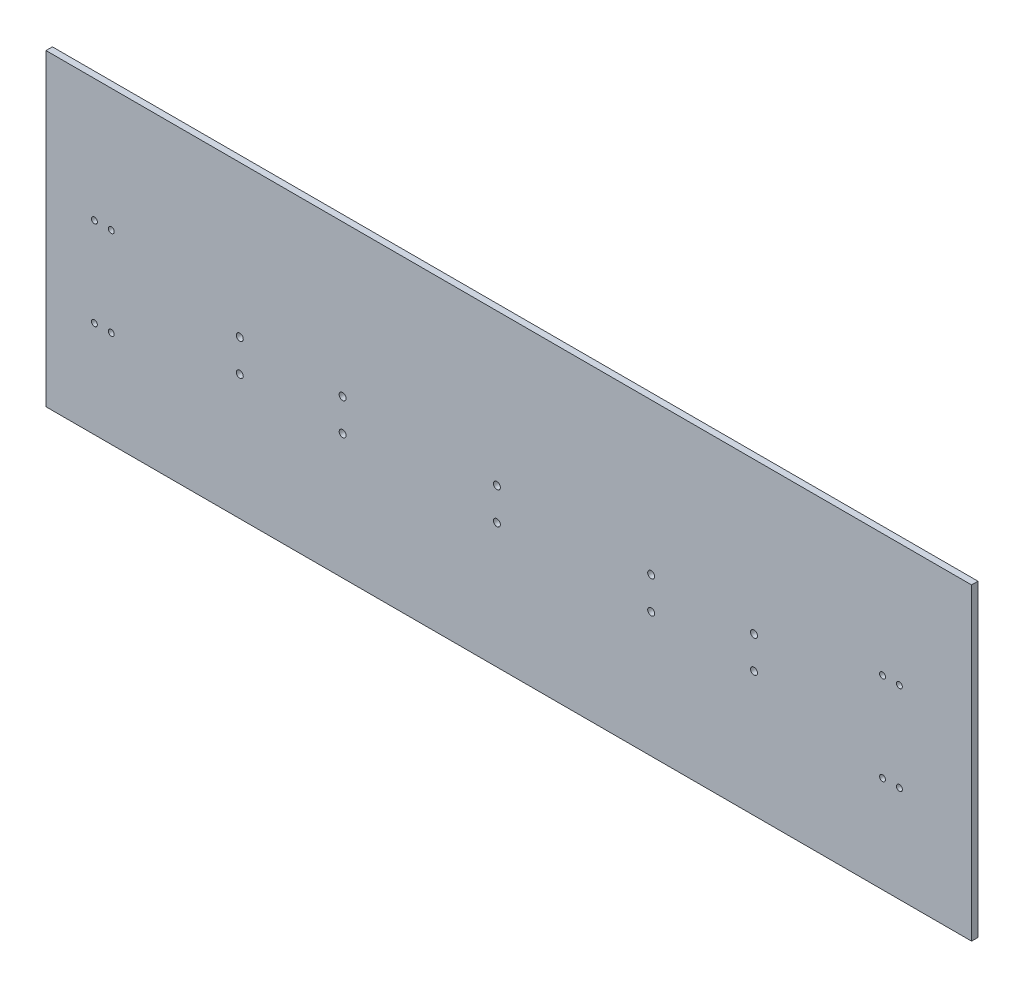
SolidWorks part; units mm, degrees
ref_plane "Front Plane" through (0, 0, 0) normal (0, 0, 1) x (1, 0, 0)
ref_plane "Top Plane" through (0, 0, 0) normal (0, 1, 0) x (1, 0, 0)
ref_plane "Right Plane" through (0, 0, 0) normal (1, 0, 0) x (0, 0, -1)
sketch "Sketch1" plane through (0, 0, 0) normal (0, 0, 1) x (1, 0, 0)
  line L0 (191.454, 155.3431) -> (191.454, 123.5931) construction
  line L1 (0, 0) -> (914.4, 0)
  line L2 (0, 0) -> (0, 304.8)
  line L3 (0, 304.8) -> (914.4, 304.8)
  line L4 (914.4, 0) -> (914.4, 304.8)
  line L5 (293.054, 155.3431) -> (293.054, 123.5931) construction
  line L6 (597.854, 155.3431) -> (597.854, 123.5931) construction
  line L7 (699.454, 155.3431) -> (699.454, 123.5931) construction
  line L8 (445.454, 155.3431) -> (445.454, 123.5931) construction
  line L9 (47.817, 183.4101) -> (64.454, 183.4101) construction
  line L10 (64.454, 183.4101) -> (64.454, 95.5261) construction
  line L11 (64.454, 95.5261) -> (47.817, 95.5261) construction
  line L12 (843.091, 183.4101) -> (826.454, 183.4101) construction
  line L13 (826.454, 183.4101) -> (826.454, 95.5261) construction
  line L14 (826.454, 95.5261) -> (843.091, 95.5261) construction
  line L15 (445.454, 139.4681) -> (597.854, 139.4681) construction
  line L16 (597.854, 139.4681) -> (699.454, 139.4681) construction
  line L17 (699.454, 139.4681) -> (826.454, 139.4681) construction
  line L18 (445.454, 139.4681) -> (293.054, 139.4681) construction
  line L19 (293.054, 139.4681) -> (191.454, 139.4681) construction
  line L20 (191.454, 139.4681) -> (64.454, 139.4681) construction
  circle A0 centre (445.454, 155.3431) radius 3.429
  circle A1 centre (445.454, 123.5931) radius 3.429
  circle A2 centre (597.854, 155.3431) radius 3.429
  circle A3 centre (597.854, 123.5931) radius 3.429
  circle A4 centre (699.454, 155.3431) radius 3.429
  circle A5 centre (699.454, 123.5931) radius 3.429
  circle A6 centre (293.054, 155.3431) radius 3.429
  circle A7 centre (293.054, 123.5931) radius 3.429
  circle A8 centre (191.454, 155.3431) radius 3.429
  circle A9 centre (191.454, 123.5931) radius 3.429
  circle A10 centre (47.817, 183.4101) radius 2.921
  circle A11 centre (64.454, 183.4101) radius 2.921
  circle A12 centre (47.817, 95.5261) radius 2.921
  circle A13 centre (64.454, 95.5261) radius 2.921
  circle A14 centre (826.454, 183.4101) radius 2.921
  circle A15 centre (843.091, 183.4101) radius 2.921
  circle A16 centre (826.454, 95.5261) radius 2.921
  circle A17 centre (843.091, 95.5261) radius 2.921
  dimension "D3" = 6.858
  dimension "D5" = 5.842
  dimension "D1" = 914.4
  dimension "D2" = 304.8
  dimension "D4" = 31.75
  dimension "D6" = 16.637
  dimension "D7" = 87.884
  dimension "D8" = 152.4
  dimension "D9" = 101.6
  dimension "D10" = 127
  dimension "D11" = 31.75
extrude "Boss-Extrude1" add sketch "Sketch1" along normal blind 6.35
